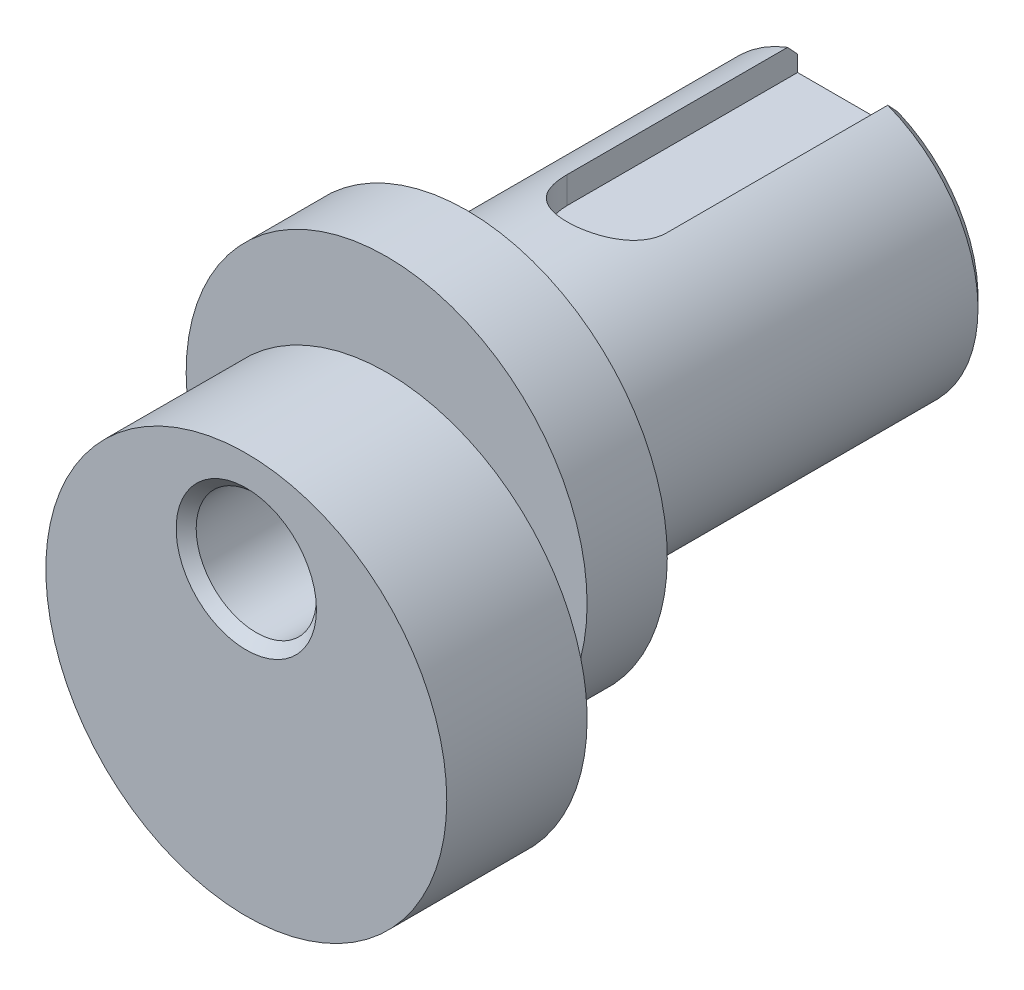
SolidWorks part; units mm, degrees
material "AISI 1035 Steel (SS)"
ref_plane "Front Plane" through (0, 0, 0) normal (0, 0, 1) x (1, 0, 0)
ref_plane "Top Plane" through (0, 0, 0) normal (0, 1, 0) x (1, 0, 0)
ref_plane "Right Plane" through (0, 0, 0) normal (1, 0, 0) x (0, 0, -1)
sketch "Sketch1" plane through (0, 0, 0) normal (0, 0, 1) x (1, 0, 0)
  circle A0 centre (0, 0) radius 10
  dimension "D1" = 20
extrude "Boss-Extrude1" add sketch "Sketch1" against normal blind 7
sketch "Sketch2" plane through (0, 0, -7) normal (0, 0, -1) x (-1, 0, 0)
  circle A0 centre (0, 5) radius 10
  dimension "D1" = 20
  dimension "D2" = 5
extrude "Boss-Extrude2" add sketch "Sketch2" along normal blind 4
sketch "Sketch3" plane through (0, 0, -11) normal (0, 0, -1) x (-1, 0, 0)
  circle A0 centre (0, 5) radius 7
  dimension "D1" = 14
extrude "Boss-Extrude3" add sketch "Sketch3" along normal blind 19
sketch "Sketch9" plane through (0, 0, 0) normal (0, 1, 0) x (1, 0, 0)
  line L0 (7, 30) -> (-7, 30) construction
  line L2 (2.5, 18.5) -> (2.5, 30)
  line L3 (2.5, 30) -> (-2.5, 30)
  line L4 (-2.5, 18.5) -> (-2.5, 30)
  arc A0 (-2.5, 18.5) -> (2.5, 18.5) centre (0, 18.5) ccw
  dimension "D3" = 5
  dimension "D1" = 11.5
  dimension "D2" = 5
extrude "Cut-Extrude5" cut sketch "Sketch9" along normal blind 10.2 from offset 10.2
chamfer "Chamfer2" distance 0.5 angle 45 1 edges at (0, -2, -30)
sketch "Sketch11" plane through (0, 0, -30) normal (0, 0, -1) x (-1, 0, 0)
  circle A0 centre (0, 5) radius 3
  dimension "D1" = 6
extrude "Cut-Extrude6" cut sketch "Sketch11" against normal through all
chamfer "Chamfer3" distance 0.5 angle 45 2 edges at (-3, 5, 0) (-3, 5, -30)
